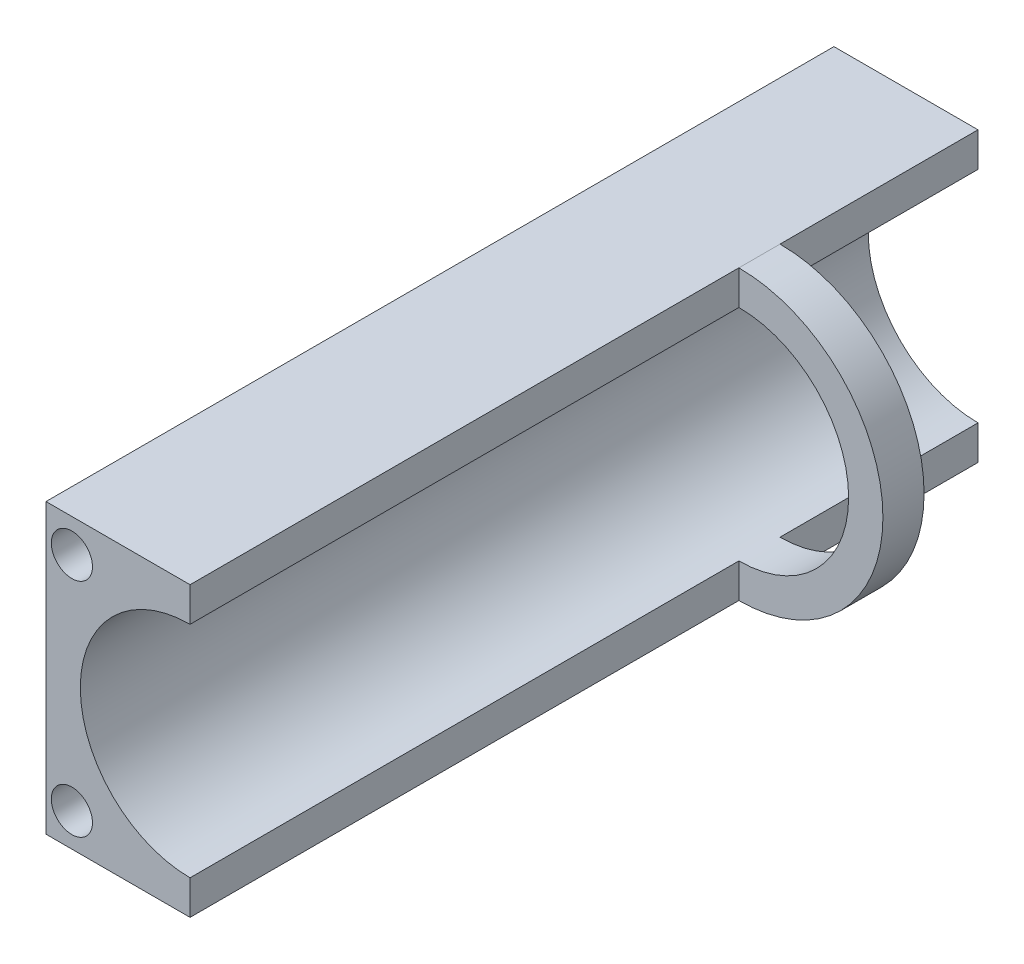
SolidWorks part; units mm, degrees
ref_plane "Front Plane" through (0, 0, 0) normal (0, 0, 1) x (1, 0, 0)
ref_plane "Top Plane" through (0, 0, 0) normal (0, 1, 0) x (1, 0, 0)
ref_plane "Right Plane" through (0, 0, 0) normal (1, 0, 0) x (0, 0, -1)
sketch "Sketch1" plane through (0, 0, 0) normal (0, 0, 1) x (1, 0, 0)
  line L0 (0, -8) -> (0, -10.5)
  line L1 (0, 10.5) -> (0, 8)
  line L2 (0, 10.5) -> (-10.5, 10.5)
  line L3 (-10.5, 10.5) -> (-10.5, -10.5)
  line L4 (-10.5, -10.5) -> (0, -10.5)
  arc A1 (0, 8) -> (0, -8) centre (0, 0) ccw
  point P3 (0, 10.5)
  point P4 (0, -10.5)
  dimension "D1" = 10.5
  dimension "D2" = 8
extrude "Boss-Extrude1" add sketch "Sketch1" along normal blind 57.43
sketch "Sketch2" plane through (0, 0, 0) normal (1, 0, 0) x (0, 0, -1)
  line L0 (-14.43, -10.5) -> (-17.43, -10.5)
  line L1 (-14.43, -10.5) -> (-14.43, -8)
  line L2 (-17.43, -10.5) -> (-17.43, -8)
  line L3 (-14.43, -8) -> (-17.43, -8)
  line L4 (-57.43, -10.5) -> (0, -10.5) construction
  line L5 (-57.43, -8) -> (-57.43, -10.5) construction
  line L6 (0, 0) -> (-50.7466, 0) construction
  line L7 (-57.43, -8) -> (0, -8) construction
  point P13 (-57.43, -9.25)
  dimension "D1" = 40
  dimension "D2" = 3
revolve "Revolve1" add sketch "Sketch2" angle 360 about L6
sketch "Sketch6" plane through (0, 0, 57.43) normal (0, 0, 1) x (1, 0, 0)
  circle A2 centre (-8.6133, 8.08) radius 1.5
  circle A3 centre (-8.6133, -8.08) radius 1.5
  point P0 (-8.6133, 8.08)
  point P1 (-8.6133, -8.08)
  dimension "D1" = 16.16
  dimension "D4" = 3
  dimension "D5" = 3
  dimension "D2" = 11.81
  dimension "D3" = 11.81
extrude "Cut-Extrude1" cut sketch "Sketch6" against normal blind 0.1
sketch "Sketch9" plane through (0, 0, 0) normal (0, 0, -1) x (-1, 0, 0)
  circle A1 centre (8.6133, 8.08) radius 1.5
  circle A2 centre (8.6133, -8.08) radius 1.5
  dimension "D1" = 16.16
  dimension "D2" = 11.81
  dimension "D5" = 11.81
extrude "Cut-Extrude2" cut sketch "Sketch9" against normal blind 0.1
hole_wizard "Ø3.0mm Dowel Hole1" positions "Sketch12" profile "Sketch13" hole size "Ø3.0" standard "ANSI Metric"
sketch "Sketch12" plane through (0, 0, 57.43) normal (0, 0, 1) x (1, 0, 0)
  point P0 (-8.6133, 8.08)
  point P3 (-8.6133, -8.08)
sketch "Sketch13" plane through (-8.6133, 8.08, 57.43) normal (1, 0, 0) x (0, -1, 0)
  line L0 (0, 0) -> (0, 3.9013)
  line L1 (0, 3.9013) -> (1.5, 3)
  line L2 (1.5, 3) -> (1.5, 0)
  line L5 (1.5, 0) -> (0, 0)
  line L10 (0, 3.9013) -> (-1.5, 3) construction
  line L11 (0, -6.35) -> (0, 107.95) construction
  dimension "Hole Dia." = 3
  dimension "Hole Depth" = 3
  dimension "Drill Angle" = 118
hole_wizard "Ø3.0mm Dowel Hole2" positions "Sketch14" profile "Sketch15" hole size "Ø3.0" standard "ANSI Metric"
sketch "Sketch14" plane through (0, 0, 0) normal (0, 0, -1) x (-1, 0, 0)
  point P0 (8.6133, 8.08)
  point P3 (8.6133, -8.08)
sketch "Sketch15" plane through (-8.6133, 8.08, 0) normal (1, 0, 0) x (0, 1, 0)
  line L0 (0, 0) -> (0, 3.9013)
  line L1 (0, 3.9013) -> (1.5, 3)
  line L2 (1.5, 3) -> (1.5, 0)
  line L5 (1.5, 0) -> (0, 0)
  line L10 (0, 3.9013) -> (-1.5, 3) construction
  line L11 (0, -6.35) -> (0, 107.95) construction
  dimension "Hole Dia." = 3
  dimension "Hole Depth" = 3
  dimension "Drill Angle" = 118
